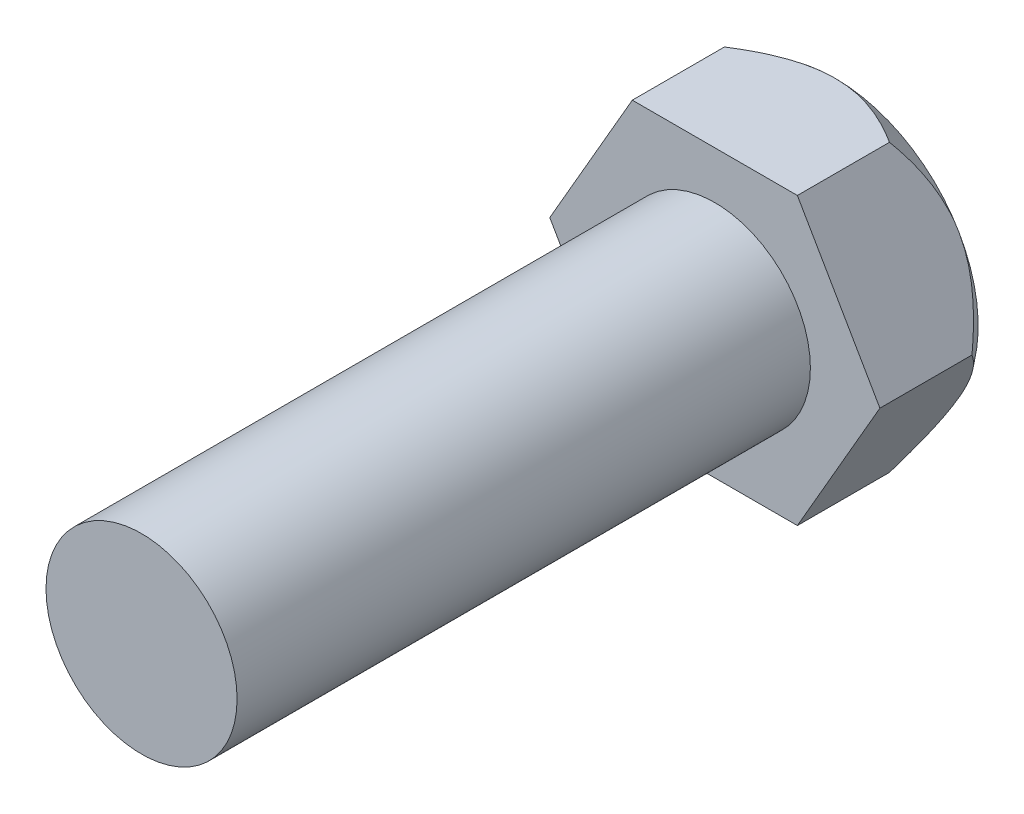
SolidWorks part; units mm, degrees
ref_plane "Alzado" through (0, 0, 0) normal (0, 0, 1) x (1, 0, 0)
ref_plane "Planta" through (0, 0, 0) normal (0, 1, 0) x (1, 0, 0)
ref_plane "Vista lateral" through (0, 0, 0) normal (1, 0, 0) x (0, 0, -1)
sketch "Croquis2" plane through (0, 0, 0) normal (0, 0, 1) x (1, 0, 0)
  line L1 (10.9697, 0) -> (5.4848, 9.5)
  line L2 (5.4848, 9.5) -> (-5.4848, 9.5)
  line L3 (-5.4848, 9.5) -> (-10.9697, 0)
  line L4 (-10.9697, 0) -> (-5.4848, -9.5)
  line L5 (-5.4848, -9.5) -> (5.4848, -9.5)
  line L6 (5.4848, -9.5) -> (10.9697, 0)
  circle A0 centre (0, 0) radius 9.5 construction
  dimension "D1" = 19
extrude "Saliente-Extruir1" add sketch "Croquis2" along normal blind 8
sketch "Croquis3" plane through (0, 0, 8) normal (0, 0, 1) x (1, 0, 0)
  circle A0 centre (0, 0) radius 6.35
  dimension "D1" = 12.7
extrude "Saliente-Extruir2" add sketch "Croquis3" along normal blind 38.1
sketch "Croquis4" plane through (0, 0, 0) normal (0, 0, -1) x (-1, 0, 0)
  circle A0 centre (0, 0) radius 9.5
  circle A1 centre (0, 0) radius 19.2796
extrude "Cortar-Extruir1" cut sketch "Croquis4" against normal blind 25.4 draft 38
